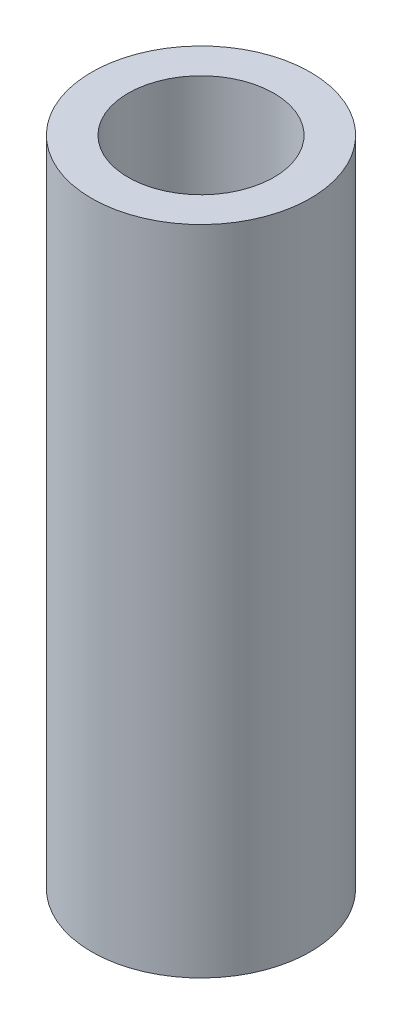
SolidWorks part; units mm, degrees
material "炭素鋼(普通)"
ref_plane "正面" through (0, 0, 0) normal (0, 0, 1) x (1, 0, 0)
ref_plane "平面" through (0, 0, 0) normal (0, 1, 0) x (1, 0, 0)
ref_plane "右側面" through (0, 0, 0) normal (1, 0, 0) x (0, 0, -1)
sketch "ｽｹｯﾁ1" plane through (0, 0, 0) normal (0, 1, 0) x (1, 0, 0)
  circle A0 centre (0, 0) radius 3
  circle A1 centre (0, 0) radius 2
  dimension "D1" = 4
  dimension "D2" = 6
extrude "ﾎﾞｽ - 押し出し1" add sketch "ｽｹｯﾁ1" along normal blind 17.9
